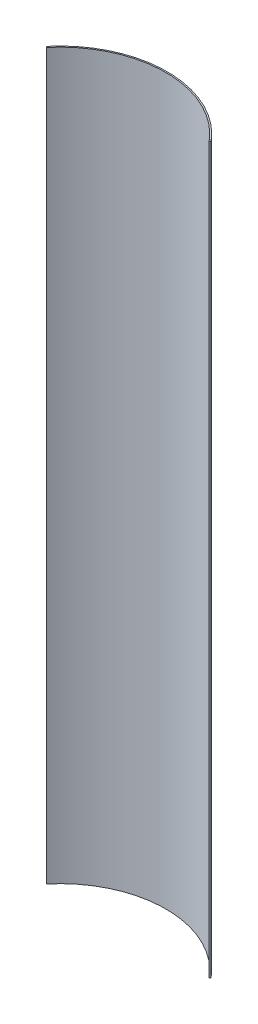
SolidWorks part; units mm, degrees
material "Custom Plastic"
ref_plane "Front Plane" through (0, 0, 0) normal (0, 0, 1) x (1, 0, 0)
ref_plane "Top Plane" through (0, 0, 0) normal (0, 1, 0) x (1, 0, 0)
ref_plane "Right Plane" through (0, 0, 0) normal (1, 0, 0) x (0, 0, -1)
sketch "Sketch1" plane through (0, 0, 0) normal (0, 1, 0) x (1, 0, 0)
  line L0 (-15.3509, 12.8199) -> (0, 0) construction
  line L1 (0, 0) -> (15.3509, 12.8199) construction
  line L6 (-15.3509, 12.8199) -> (-15.1559, 12.6571)
  line L7 (15.3509, 12.8199) -> (15.1559, 12.6571)
  arc A0 (-15.3509, 12.8199) -> (15.3509, 12.8199) centre (0, 0) cw
  arc A2 (-15.1559, 12.6571) -> (15.1559, 12.6571) centre (0, 0) cw
  dimension "D1" = 20
  dimension "D2" = 100.268
  dimension "D3" = 0.254
extrude "Boss-Extrude1" add sketch "Sketch1" along normal blind 135
